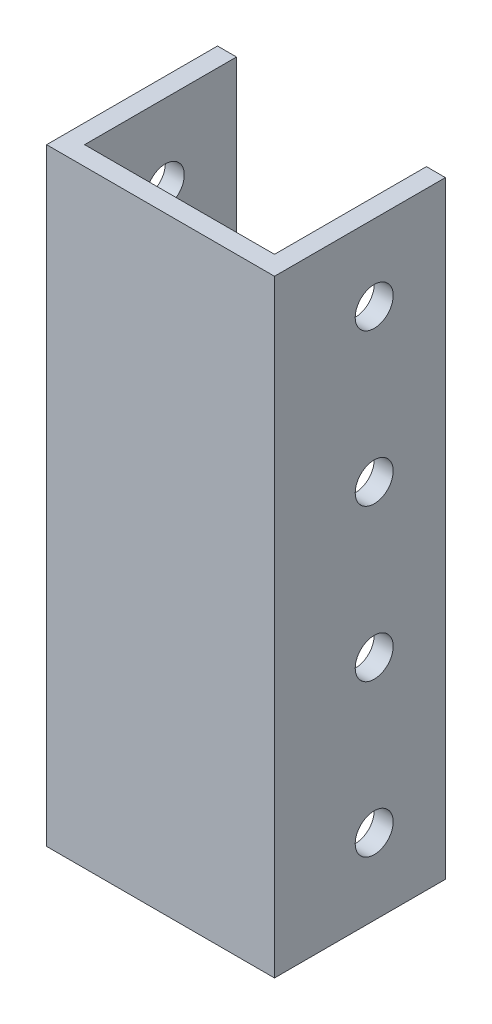
SolidWorks part; units mm, degrees
ref_plane "Front Plane" through (0, 0, 0) normal (0, 0, 1) x (1, 0, 0)
ref_plane "Top Plane" through (0, 0, 0) normal (0, 1, 0) x (1, 0, 0)
ref_plane "Right Plane" through (0, 0, 0) normal (1, 0, 0) x (0, 0, -1)
sketch "Sketch1" plane through (0, 0, 0) normal (0, 1, 0) x (1, 0, 0)
  line L0 (0, 0) -> (0, 28.575)
  line L1 (34.925, 28.575) -> (34.925, 3.175)
  line L2 (34.925, 3.175) -> (3.175, 3.175)
  line L3 (3.175, 3.175) -> (3.175, 28.575)
  line L4 (0, 28.575) -> (3.175, 28.575)
  line L5 (34.925, 28.575) -> (38.1, 28.575)
  line L6 (38.1, 28.575) -> (38.1, 0)
  line L7 (38.1, 0) -> (0, 0)
  dimension "D1" = 3.175
  dimension "D2" = 28.575
  dimension "D4" = 38.1
extrude "Boss-Extrude1" add sketch "Sketch1" along normal blind 101.6
sketch "Sketch3" plane through (0, 0, 0) normal (-1, 0, 0) x (0, 0, 1)
  line L0 (-28.575, 0) -> (0, 0) construction
  line L1 (0, 101.6) -> (0, 0) construction
  circle A0 centre (-16.6687, 12.7) radius 3.175
  circle A1 centre (-16.6687, 38.1) radius 3.175
  circle A2 centre (-16.6687, 63.5) radius 3.175
  circle A3 centre (-16.6687, 88.9) radius 3.175
  dimension "D1" = 12.7
  dimension "D2" = 16.6687
  dimension "D3" = 6.35
  dimension "D4" = 4
extrude "Cut-Extrude1" cut sketch "Sketch3" against normal through all
